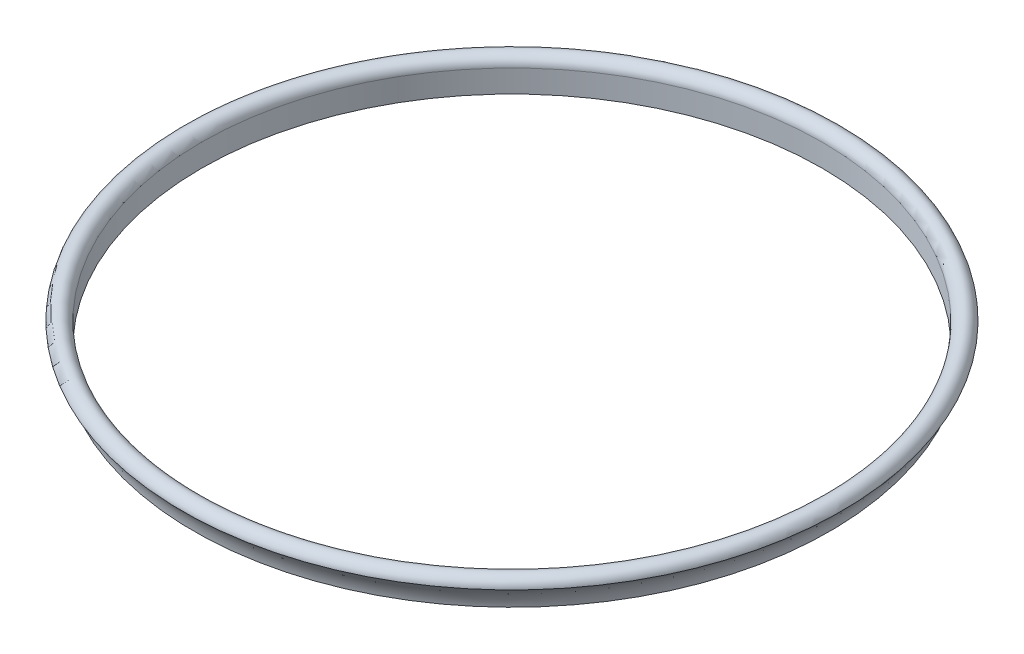
SolidWorks part; units mm, degrees
material "ABS"
ref_plane "Front Plane" through (0, 0, 0) normal (0, 0, 1) x (1, 0, 0)
ref_plane "Top Plane" through (0, 0, 0) normal (0, 1, 0) x (1, 0, 0)
ref_plane "Right Plane" through (0, 0, 0) normal (1, 0, 0) x (0, 0, -1)
sketch "Sketch1" plane through (0, 0, 0) normal (0, 0, 1) x (1, 0, 0)
  line L7 (82.55, 0) -> (82.55, 6)
  line L8 (84.582, 0) -> (82.55, 0)
  line L9 (0, 0) -> (0, 14.8903) construction
  arc A0 (82.55, 6) -> (87.6262, 6.1383) centre (85.09, 6) cw
  arc A3 (87.6262, 6.1383) -> (84.582, 0) centre (94.5208, -1.105) ccw
  dimension "D1" = 2.032
  dimension "D3" = 2.54
  dimension "D4" = 10
  dimension "D2" = 6
  dimension "D5" = 82.55
revolve "Revolve1" add sketch "Sketch1" angle 360 about L9
